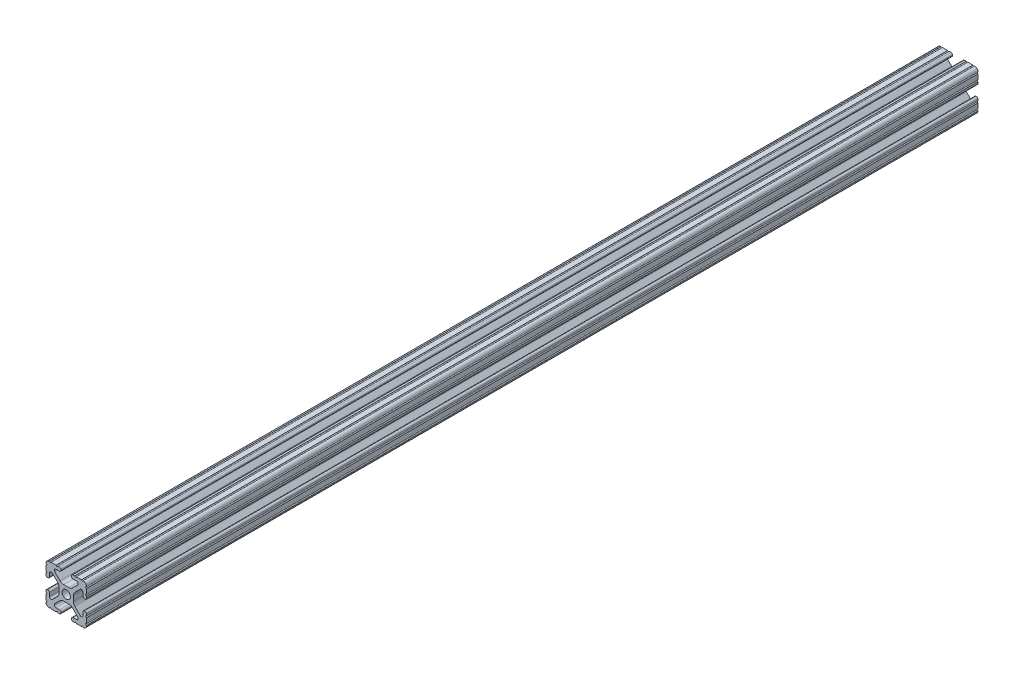
SolidWorks part; units mm, degrees
ref_plane "Front Plane" through (0, 0, 0) normal (0, 0, 1) x (1, 0, 0)
ref_plane "Top Plane" through (0, 0, 0) normal (0, 1, 0) x (1, 0, 0)
ref_plane "Right Plane" through (0, 0, 0) normal (1, 0, 0) x (0, 0, -1)
sketch "Sketch1" plane through (0, 0, 0) normal (0, 0, 1) x (1, 0, 0)
  line L0 (-7.207, 8.7244) -> (-3.8983, 5.4232)
  line L1 (-4.2875, 10.4902) -> (-6.4768, 10.4902)
  line L2 (-3.2385, 11.651) -> (-3.2385, 11.5392)
  line L3 (-5.3171, 12.7) -> (-4.2875, 12.7)
  line L4 (0, 13.4005) -> (0, -14.8534) construction
  line L5 (12.7, 0) -> (-13.9989, 0) construction
  line L6 (-9.5504, 12.7) -> (-6.3331, 12.7)
  line L7 (-12.7, 6.3331) -> (-12.7, 9.5504)
  line L8 (-12.7, 4.2875) -> (-12.7, 5.3171)
  line L9 (-11.5392, 3.2385) -> (-11.651, 3.2385)
  line L10 (-10.4902, 6.4021) -> (-10.4902, 4.2875)
  line L11 (-5.441, 3.8408) -> (-8.7371, 7.1294)
  line L12 (-4.5085, -1.5932) -> (-4.5085, 1.5932)
  line L13 (-1.7093, -4.4958) -> (1.7093, -4.4958)
  line L14 (3.9523, -5.4237) -> (7.1797, -8.6452)
  line L15 (6.4164, -10.4902) -> (4.2875, -10.4902)
  line L16 (3.2385, -11.5392) -> (3.2385, -11.651)
  line L17 (4.2875, -12.7) -> (5.3171, -12.7)
  line L18 (6.3331, -12.7) -> (9.5504, -12.7)
  line L19 (12.7, -9.5504) -> (12.7, -6.3331)
  line L20 (12.7, -5.3171) -> (12.7, -4.2875)
  line L21 (11.651, -3.2385) -> (11.5392, -3.2385)
  line L22 (10.4902, -4.2875) -> (10.4902, -6.4021)
  line L23 (8.7371, -7.1294) -> (5.441, -3.8408)
  line L24 (4.5085, -1.5932) -> (4.5085, 1.5932)
  line L25 (5.441, 3.8408) -> (8.7371, 7.1294)
  line L26 (10.4902, 6.4021) -> (10.4902, 4.2875)
  line L27 (11.5392, 3.2385) -> (11.651, 3.2385)
  line L28 (12.7, 4.2875) -> (12.7, 5.3171)
  line L29 (12.7, 6.3331) -> (12.7, 9.5504)
  line L30 (9.5504, 12.7) -> (6.3331, 12.7)
  line L31 (5.3171, 12.7) -> (4.2875, 12.7)
  line L32 (3.2385, 11.651) -> (3.2385, 11.5392)
  line L33 (4.2875, 10.4902) -> (6.4768, 10.4902)
  line L34 (7.207, 8.7244) -> (3.8983, 5.4232)
  line L35 (1.6558, 4.4958) -> (-1.6558, 4.4958)
  line L36 (-8.7371, -7.1294) -> (-5.441, -3.8408)
  line L37 (-10.4902, -4.2875) -> (-10.4902, -6.4021)
  line L38 (-11.651, -3.2385) -> (-11.5392, -3.2385)
  line L39 (-12.7, -5.3171) -> (-12.7, -4.2875)
  line L40 (-12.7, -9.5504) -> (-12.7, -6.3331)
  line L41 (-6.3331, -12.7) -> (-9.5504, -12.7)
  line L42 (-4.2875, -12.7) -> (-5.3171, -12.7)
  line L43 (-3.2385, -11.5392) -> (-3.2385, -11.651)
  line L44 (-6.4164, -10.4902) -> (-4.2875, -10.4902)
  line L45 (-3.9523, -5.4237) -> (-7.1797, -8.6452)
  arc A0 (-7.207, 8.7244) -> (-6.4768, 10.4902) centre (-6.4768, 9.4563) cw
  arc A1 (-3.2385, 11.5392) -> (-4.2875, 10.4902) centre (-4.2875, 11.5392) cw
  arc A2 (-4.2875, 12.7) -> (-3.2385, 11.651) centre (-4.2875, 11.651) cw
  arc A3 (-5.3171, 12.7) -> (-6.3331, 12.7) centre (-5.8251, 12.7) cw
  arc A4 (-9.5504, 12.7) -> (-10.5664, 12.6998) centre (-10.0584, 12.7) cw
  arc A5 (-12.6998, 10.5664) -> (-10.5664, 12.6998) centre (-10.5918, 10.5918) cw
  arc A6 (-12.6998, 10.5664) -> (-12.7, 9.5504) centre (-12.7, 10.0584) cw
  arc A7 (-12.7, 6.3331) -> (-12.7, 5.3171) centre (-12.7, 5.8251) cw
  arc A8 (-11.651, 3.2385) -> (-12.7, 4.2875) centre (-11.651, 4.2875) cw
  arc A9 (-10.4902, 4.2875) -> (-11.5392, 3.2385) centre (-11.5392, 4.2875) cw
  circle A10 centre (0, 0) radius 2.6035
  arc A11 (-10.4902, 6.4021) -> (-8.7371, 7.1294) centre (-9.4628, 6.4021) cw
  arc A12 (-5.441, 3.8408) -> (-4.5085, 1.5932) centre (-7.6835, 1.5932) cw
  arc A13 (-4.5085, -1.5932) -> (-5.441, -3.8408) centre (-7.6835, -1.5932) cw
  arc A14 (-8.7371, -7.1294) -> (-10.4902, -6.4021) centre (-9.4628, -6.4021) cw
  arc A15 (-1.7093, -4.4958) -> (-3.9523, -5.4237) centre (-1.7093, -7.6708) ccw
  arc A16 (3.9523, -5.4237) -> (1.7093, -4.4958) centre (1.7093, -7.6708) ccw
  arc A17 (6.4164, -10.4902) -> (7.1797, -8.6452) centre (6.4164, -9.4098) ccw
  arc A18 (4.2875, -10.4902) -> (3.2385, -11.5392) centre (4.2875, -11.5392) ccw
  arc A19 (3.2385, -11.651) -> (4.2875, -12.7) centre (4.2875, -11.651) ccw
  arc A20 (6.3331, -12.7) -> (5.3171, -12.7) centre (5.8251, -12.7) ccw
  arc A21 (10.5664, -12.6998) -> (9.5504, -12.7) centre (10.0584, -12.7) ccw
  arc A22 (10.5664, -12.6998) -> (12.6998, -10.5664) centre (10.5918, -10.5918) ccw
  arc A23 (12.7, -9.5504) -> (12.6998, -10.5664) centre (12.7, -10.0584) ccw
  arc A24 (12.7, -5.3171) -> (12.7, -6.3331) centre (12.7, -5.8251) ccw
  arc A25 (12.7, -4.2875) -> (11.651, -3.2385) centre (11.651, -4.2875) ccw
  arc A26 (11.5392, -3.2385) -> (10.4902, -4.2875) centre (11.5392, -4.2875) ccw
  arc A27 (8.7371, -7.1294) -> (10.4902, -6.4021) centre (9.4628, -6.4021) ccw
  arc A28 (4.5085, -1.5932) -> (5.441, -3.8408) centre (7.6835, -1.5932) ccw
  arc A29 (5.441, 3.8408) -> (4.5085, 1.5932) centre (7.6835, 1.5932) ccw
  arc A30 (10.4902, 6.4021) -> (8.7371, 7.1294) centre (9.4628, 6.4021) ccw
  arc A31 (10.4902, 4.2875) -> (11.5392, 3.2385) centre (11.5392, 4.2875) ccw
  arc A32 (11.651, 3.2385) -> (12.7, 4.2875) centre (11.651, 4.2875) ccw
  arc A33 (12.7, 6.3331) -> (12.7, 5.3171) centre (12.7, 5.8251) ccw
  arc A34 (12.6998, 10.5664) -> (12.7, 9.5504) centre (12.7, 10.0584) ccw
  arc A35 (12.6998, 10.5664) -> (10.5664, 12.6998) centre (10.5918, 10.5918) ccw
  arc A36 (9.5504, 12.7) -> (10.5664, 12.6998) centre (10.0584, 12.7) ccw
  arc A37 (5.3171, 12.7) -> (6.3331, 12.7) centre (5.8251, 12.7) ccw
  arc A38 (4.2875, 12.7) -> (3.2385, 11.651) centre (4.2875, 11.651) ccw
  arc A39 (3.2385, 11.5392) -> (4.2875, 10.4902) centre (4.2875, 11.5392) ccw
  arc A40 (7.207, 8.7244) -> (6.4768, 10.4902) centre (6.4768, 9.4563) ccw
  arc A41 (1.6558, 4.4958) -> (3.8983, 5.4232) centre (1.6558, 7.6708) ccw
  arc A42 (-1.6558, 4.4958) -> (-3.8983, 5.4232) centre (-1.6558, 7.6708) cw
  arc A43 (-11.5392, -3.2385) -> (-10.4902, -4.2875) centre (-11.5392, -4.2875) cw
  arc A44 (-12.7, -4.2875) -> (-11.651, -3.2385) centre (-11.651, -4.2875) cw
  arc A45 (-12.7, -5.3171) -> (-12.7, -6.3331) centre (-12.7, -5.8251) cw
  arc A46 (-12.7, -9.5504) -> (-12.6998, -10.5664) centre (-12.7, -10.0584) cw
  arc A47 (-10.5664, -12.6998) -> (-12.6998, -10.5664) centre (-10.5918, -10.5918) cw
  arc A48 (-10.5664, -12.6998) -> (-9.5504, -12.7) centre (-10.0584, -12.7) cw
  arc A49 (-6.3331, -12.7) -> (-5.3171, -12.7) centre (-5.8251, -12.7) cw
  arc A50 (-3.2385, -11.651) -> (-4.2875, -12.7) centre (-4.2875, -11.651) cw
  arc A51 (-4.2875, -10.4902) -> (-3.2385, -11.5392) centre (-4.2875, -11.5392) cw
  arc A52 (-6.4164, -10.4902) -> (-7.1797, -8.6452) centre (-6.4164, -9.4098) cw
  dimension "D1" = 5.207
  dimension "D9" = 14.859
  dimension "D2" = 25.4
  dimension "D3" = 12.7
  dimension "D4" = 6.477
  dimension "D5" = 8.2042
  dimension "D6" = 9.017
  dimension "D8" = 2.2098
  dimension "D10" = 2.2098
extrude "Extrude1" add sketch "Sketch1" against normal blind 558.8 and the other way blind 0.508
